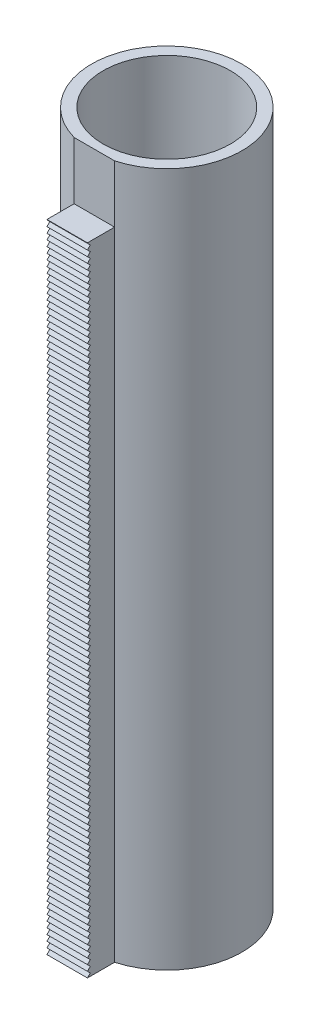
SolidWorks part; units mm, degrees
material "Aleación 1060"
ref_plane "Alzado" through (0, 0, 0) normal (0, 0, 1) x (1, 0, 0)
ref_plane "Planta" through (0, 0, 0) normal (0, 1, 0) x (1, 0, 0)
ref_plane "Vista lateral" through (0, 0, 0) normal (1, 0, 0) x (0, 0, -1)
sketch "Croquis1" plane through (0, 0, 0) normal (0, 1, 0) x (1, 0, 0)
  line L0 (0, 0) -> (0, -25.7967) construction
  line L3 (-3.5, -12.52) -> (-3.5, -17.22)
  line L4 (-3.5, -17.22) -> (3.5, -17.22)
  line L5 (3.5, -12.52) -> (3.5, -17.22)
  arc A0 (3.5, -12.52) -> (-3.5, -12.52) centre (0, 0) ccw
  circle A1 centre (0, 0) radius 11
  dimension "D1" = 26
  dimension "D2" = 22
  dimension "D3" = 7
  dimension "D4" = 4.7
extrude "Saliente-Extruir1" add sketch "Croquis1" along normal blind 120
sketch "Croquis3" plane through (3.5, 0, 0) normal (1, 0, 0) x (0, 0, -1)
  line L0 (-17.22, 110) -> (-12.52, 110)
  line L1 (-17.22, 120) -> (-17.22, 0) construction
  line L2 (-12.52, 120) -> (-12.52, 0) construction
  line L3 (-12.52, 110) -> (-12.52, 120)
  line L4 (-12.52, 120) -> (-22.111, 120)
  line L5 (-22.111, 120) -> (-22.111, 0)
  line L6 (-22.111, 0) -> (-17.22, 0)
  line L7 (-17.22, 109.5) -> (-16.22, 109.5) construction
  line L8 (-17.22, 110) -> (-16.72, 109.5)
  line L9 (-16.72, 109.5) -> (-17.22, 109)
  line L10 (-17.22, 110) -> (-17.22, 109)
  line M229 (-17.22, 120) -> (-17.22, 0)
  dimension "D1" = 10
  dimension "D2" = 0.5
extrude "Cortar-Extruir1" cut sketch "Croquis3" against normal blind 120 contours L7 L10 L9 | L7 L8 M229
pattern_linear "MatrizL1" count 120 spacing 1 along (0, -1, 0) of "Cortar-Extruir1"
sketch "Croquis4" plane through (3.5, 0, 0) normal (1, 0, 0) x (0, 0, -1)
  line L1 (-17.22, 120) -> (-12.52, 120)
  line L2 (-17.22, 120) -> (-17.22, 110.0768)
  line L3 (-17.22, 110.0768) -> (-12.52, 110.0768)
  line L4 (-12.52, 120) -> (-12.52, 110.0768)
extrude "Cortar-Extruir2" cut sketch "Croquis4" against normal blind 120
ref_plane "Plano1" through (0, 115.0768, 0) normal (0, 1, 0) x (1, 0, 0)
